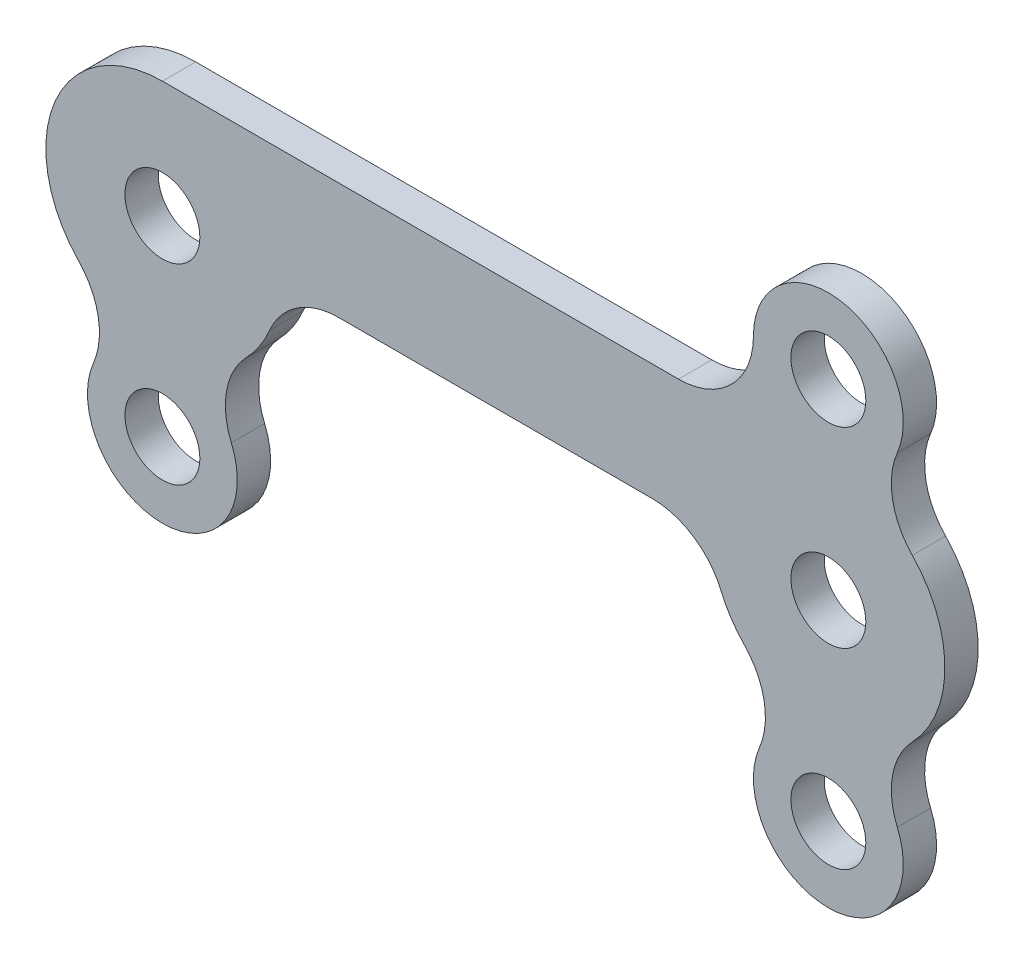
SolidWorks part; units mm, degrees
ref_plane "Front Plane" through (0, 0, 0) normal (0, 0, 1) x (1, 0, 0)
ref_plane "Top Plane" through (0, 0, 0) normal (0, 1, 0) x (1, 0, 0)
ref_plane "Right Plane" through (0, 0, 0) normal (1, 0, 0) x (0, 0, -1)
sketch "Sketch1" plane through (0, 0, 0) normal (0, 0, 1) x (1, 0, 0)
  line L11 (5.5562, 0) -> (26.1938, 0)
  line L12 (0, 5.5563) -> (31.75, 5.5563)
  circle A27 centre (0, 0) radius 5.5563 construction
  circle A28 centre (31.75, 0) radius 5.5562 construction
  arc A29 (0, 5.5563) -> (0, -5.5562) centre (0, 0) ccw
  arc A30 (31.75, -5.5563) -> (31.75, 5.5563) centre (31.75, 0) ccw
  circle A31 centre (0, 0) radius 1.7859
  circle A32 centre (31.75, 0) radius 1.7859
  arc A33 (0, -5.5562) -> (5.5562, 0) centre (0, 0) ccw
  arc A34 (26.1938, 0) -> (31.75, -5.5563) centre (31.75, 0) ccw
  circle A35 centre (0, -9.1281) radius 3.5719
  circle A36 centre (31.75, -9.1281) radius 1.7859
  circle A37 centre (0, -9.1281) radius 1.7859
  circle A38 centre (31.75, -9.1281) radius 3.5719
  circle A39 centre (-6.5741, -6.3327) radius 3.5719
  circle A40 centre (6.5741, -6.3327) radius 3.5719
  circle A41 centre (25.1759, -6.3327) radius 3.5719
  circle A42 centre (38.3241, -6.3327) radius 3.5719
  circle A43 centre (31.75, 9.1281) radius 1.7859
  circle A44 centre (31.75, 9.1281) radius 3.5719
  circle A45 centre (24.6062, 9.1281) radius 3.5719
  circle A46 centre (38.3241, 6.3327) radius 3.5719
  point P0 (0, 0)
  dimension "D8" = 31.75
  dimension "D9" = 11.1125
  dimension "D10" = 3.5719
  dimension "D11" = 7.1437
  dimension "D12" = 3.5719
extrude "Boss-Extrude1" add sketch "Sketch1" along normal blind 1.5875 contours L11 A34 A30 L12 A29 A33 A31 A32 | A35 A37 | A38 A36 | A44 A43 | A45 L12 A44 | A46 A44 A30 | A42 A30 A38 | A41 A38 A34 | A40 A33 A35 | A39 A35 A29
fillet "Fillet1" radius 3.5719 2 edges at (26.1938, 0, 0.7937) (5.5562, 0, 0.7937)
